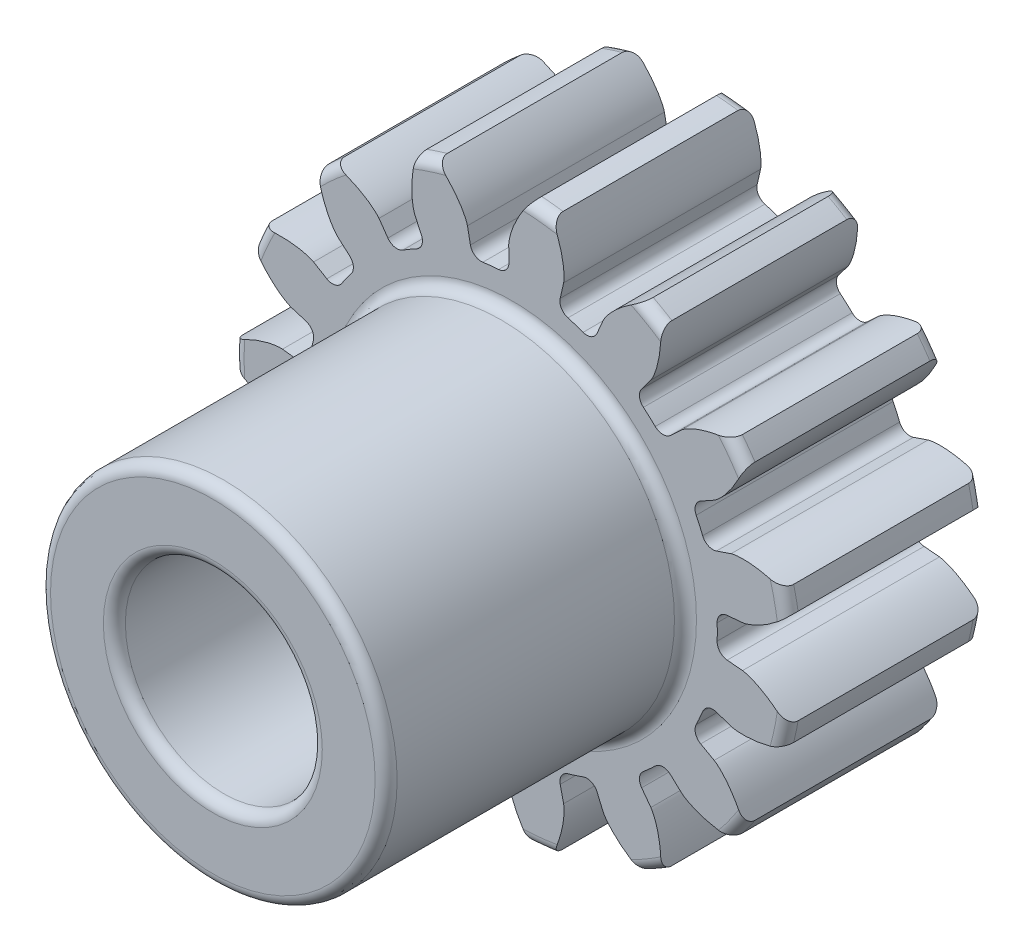
SolidWorks part; units mm, degrees
ref_plane "Front Plane" through (0, 0, 0) normal (0, 0, 1) x (1, 0, 0)
ref_plane "Top Plane" through (0, 0, 0) normal (0, 1, 0) x (1, 0, 0)
ref_plane "Right Plane" through (0, 0, 0) normal (1, 0, 0) x (0, 0, -1)
sketch "Sketch1" plane through (0, 0, 0) normal (0, 0, 1) x (1, 0, 0)
  line L0 (0, 0) -> (0, 3.9688) construction
  line L1 (-1.2755, 4.433) -> (1.2755, 3.5045) construction
  circle A0 centre (0, 0) radius 3.3073 construction
  circle A1 centre (0, 0) radius 4.4979 construction
  circle A2 centre (0, 0) radius 3.9688 construction
  circle A3 centre (0, 0) radius 3.7294 construction
  circle A4 centre (0, 0) radius 1.5875 construction
  circle A5 centre (0, 0) radius 2.794 construction
  point P8 (609.6, 0)
  point P13 (190.5, 0)
  dimension "OD | Outside Diameter" = 8.9958
  dimension "Root Diameter" = 6.6146
  dimension "Gear Pitch Diameter" = 7.9375
  dimension "Base Diameter" = 7.4588
  dimension "For Shaft Diameter" = 3.175
  dimension "Hub Diameter" = 5.588
  dimension "Pressure Angle" = 20
  dimension "Number of Teeth" = 381
  dimension "Gear Pitch | Diametral Pitch" = 1219.2
sketch "Sketch2" plane through (0, 0, 0) normal (1, 0, 0) x (0, 0, -1)
  line L0 (-4.0005, 0) -> (4.0005, 0) construction
  line L1 (-4.0005, 4.4979) -> (4.0005, 4.4979) construction
  point P2 (0, 4.4979)
  point P4 (0.8255, 0)
  point P6 (0.8255, 4.4979)
  dimension "Overall Width" = 8.001
  dimension "Hub Width" = 4.826
  dimension "Face Width" = 3.175
sketch "Sketch3" plane through (0, 0, 0) normal (0, 0, 1) x (1, 0, 0)
  circle A0 centre (0, 0) radius 4.4979
  circle A1 centre (0, 0) radius 4.4979 construction
extrude "Boss-Extrude1" add sketch "Sketch3" against normal up to vertex (4.0005 mm away) and the other way up to vertex (4.0005 mm away) up to point (0, 0, -4.0005) other way up to point (0, 0, 4.0005)
sketch "Sketch5" plane through (0, 0, 0) normal (1, 0, 0) x (0, 0, -1)
  line L1 (-4.0005, 4.4979) -> (0.8255, 4.4979)
  line L2 (-4.0005, 4.4979) -> (-4.0005, 2.794)
  line L3 (-4.0005, 2.794) -> (0.8255, 2.794)
  line L4 (0.8255, 4.4979) -> (0.8255, 2.794)
  line L11 (4.0005, 1.5875) -> (-4.0005, 1.5875)
  line L12 (4.0005, 1.5875) -> (4.0005, 0)
  line L13 (4.0005, 0) -> (-4.0005, 0)
  line L14 (-4.0005, 1.5875) -> (-4.0005, 0)
  point P5 (0, 1.5875)
  point P12 (0, 2.794)
revolve "Cut-Revolve1" cut sketch "Sketch5" angle 360 about L0
fillet "Fillet2" radius 0.1775 6 edges at (4.4979, 0, -4.0005) (1.5875, 0, -4.0005) (1.5875, 0, 4.0005) (2.794, 0, -0.8255) (4.4979, 0, -0.8255) (2.794, 0, 4.0005)
sketch "Sketch4" plane through (0, 0, 0) normal (0, 0, 1) x (1, 0, 0)
  line L0 (0, 0) -> (3.294, 0.2966) construction
  line L2 (0, 0) -> (3.294, -0.2966) construction
  line L4 (3.294, 0.2966) -> (3.7144, 0.3345)
  line L5 (3.7144, -0.3345) -> (3.294, -0.2966)
  arc A0 (3.294, 0.2966) -> (3.294, -0.2966) centre (0, 0) cw
  arc A3 (4.4324, 0.7646) -> (4.4324, -0.7646) centre (0, 0) cw
  circle A4 centre (0, 0) radius 4.4979 construction
  spline S0 degree 4 poles (3.7144, 0.3345) (3.7156, 0.3346) (3.7191, 0.3351) (3.7257, 0.3361) (3.7364, 0.338) (3.7499, 0.341) (3.7674, 0.3453) (3.7878, 0.3511) (3.8101, 0.3581) (3.8341, 0.3665) (3.858, 0.3755) (3.8817, 0.3851) (3.9051, 0.3952) (3.9333, 0.4081) (3.9668, 0.4244) (4.0056, 0.4448) (4.0491, 0.4694) (4.0929, 0.496) (4.1354, 0.5236) (4.1779, 0.5529) (4.2185, 0.5823) (4.2601, 0.6144) (4.2981, 0.6447) (4.34, 0.6803) (4.3736, 0.7095) (4.417, 0.7498) (4.4424, 0.7741) (4.4719, 0.8031) (4.4848, 0.8163) (4.4928, 0.8244) knots 0 0 0 0 0 0.005377 0.015084 0.028532 0.04661 0.064855 0.092111 0.119476 0.146842 0.174209 0.201575 0.228941 0.256307 0.307035 0.361767 0.4165 0.471232 0.525964 0.580697 0.635429 0.690161 0.744894 0.799626 0.854358 0.909091 0.954545 1 1 1 1 1 construction
  spline S1 degree 4 poles (3.7144, 0.3345) (3.7156, 0.3346) (3.7191, 0.3351) (3.7257, 0.3361) (3.7364, 0.338) (3.7499, 0.341) (3.7674, 0.3453) (3.7878, 0.3511) (3.8101, 0.3581) (3.8341, 0.3665) (3.858, 0.3755) (3.8817, 0.3851) (3.9051, 0.3952) (3.9333, 0.4081) (3.9668, 0.4244) (4.0056, 0.4448) (4.0491, 0.4694) (4.0929, 0.496) (4.1354, 0.5236) (4.1779, 0.5529) (4.2185, 0.5823) (4.2601, 0.6144) (4.2981, 0.6447) (4.34, 0.6803) (4.3736, 0.7095) (4.4076, 0.7411) (4.4241, 0.7566) (4.4324, 0.7646) knots 0 0 0 0 0 0.005377 0.015084 0.028532 0.04661 0.064855 0.092111 0.119476 0.146842 0.174209 0.201575 0.228941 0.256307 0.307035 0.361767 0.4165 0.471232 0.525964 0.580697 0.635429 0.690161 0.744894 0.799626 0.854358 0.909091 0.909091 0.909091 0.909091 0.909091
  spline S2 degree 4 poles (3.7144, -0.3345) (3.7156, -0.3346) (3.7191, -0.3351) (3.7257, -0.3361) (3.7364, -0.338) (3.7499, -0.341) (3.7674, -0.3453) (3.7878, -0.3511) (3.8101, -0.3581) (3.8341, -0.3665) (3.858, -0.3755) (3.8817, -0.3851) (3.9051, -0.3952) (3.9333, -0.4081) (3.9668, -0.4244) (4.0056, -0.4448) (4.0491, -0.4694) (4.0929, -0.496) (4.1354, -0.5236) (4.1779, -0.5529) (4.2185, -0.5823) (4.2601, -0.6144) (4.2981, -0.6447) (4.34, -0.6803) (4.3736, -0.7095) (4.417, -0.7498) (4.4424, -0.7741) (4.4719, -0.8031) (4.4848, -0.8163) (4.4928, -0.8244) knots 0 0 0 0 0 0.005377 0.015084 0.028532 0.04661 0.064855 0.092111 0.119476 0.146842 0.174209 0.201575 0.228941 0.256307 0.307035 0.361767 0.4165 0.471232 0.525964 0.580697 0.635429 0.690161 0.744894 0.799626 0.854358 0.909091 0.954545 1 1 1 1 1 construction
  spline S3 degree 4 poles (3.7144, -0.3345) (3.7156, -0.3346) (3.7191, -0.3351) (3.7257, -0.3361) (3.7364, -0.338) (3.7499, -0.341) (3.7674, -0.3453) (3.7878, -0.3511) (3.8101, -0.3581) (3.8341, -0.3665) (3.858, -0.3755) (3.8817, -0.3851) (3.9051, -0.3952) (3.9333, -0.4081) (3.9668, -0.4244) (4.0056, -0.4448) (4.0491, -0.4694) (4.0929, -0.496) (4.1354, -0.5236) (4.1779, -0.5529) (4.2185, -0.5823) (4.2601, -0.6144) (4.2981, -0.6447) (4.34, -0.6803) (4.3736, -0.7095) (4.4076, -0.7411) (4.4241, -0.7566) (4.4324, -0.7646) knots 0 0 0 0 0 0.005377 0.015084 0.028532 0.04661 0.064855 0.092111 0.119476 0.146842 0.174209 0.201575 0.228941 0.256307 0.307035 0.361767 0.4165 0.471232 0.525964 0.580697 0.635429 0.690161 0.744894 0.799626 0.854358 0.909091 0.909091 0.909091 0.909091 0.909091
  dimension "D1" = 6.6146
extrude "Cut-Extrude1" cut sketch "Sketch4" against normal through all both and the other way through all
fillet "Fillet1" radius 0.1775 2 edges at (3.294, -0.2966, -2.413) (3.294, 0.2966, -2.413)
pattern_circular "CirPattern1" count 15 over 360 about axis through (0, 0, 4.0005) along (0, 0, -1) of "Cut-Extrude1", "Fillet1"
equation "\"Root Diameter@Sketch1\"=\"Root Diameter\""
equation "\"OD | Outside Diameter@Sketch1\"=\"Outside Diameter\""
equation "\"D1@CirPattern1\"=\"Number of Teeth\""
equation "\"Diametral Pitch\"= 48"
equation "\"Number of Teeth\"= 15"
equation "\"Pressure Angle\"=20"
equation "\"Pitch Diameter\"= \"Number of Teeth\" / \"Diametral Pitch\""
equation "\"Base Diameter\"= \"Pitch Diameter\" * cos ( \"Pressure Angle\" )"
equation "\"Outside Diameter\"= ( \"Number of Teeth\" + 2 ) / \"Diametral Pitch\""
equation "\"Dedendum\"= 1.25 / \"Diametral Pitch\""
equation "\"Root Diameter\"= \"Pitch Diameter\" - ( 2 * \"Dedendum\" )"
equation "\"Pitch Angle\"= 360deg / \"Number of Teeth\""
equation "\"Alpha\"= sqr ( \"Pitch Diameter\" ^ 2 - \"Base Diameter\" ^ 2 ) / \"Base Diameter\" * 180 / PI - \"Pressure Angle\""
equation "\"Beta\"= ( \"Pitch Angle\" / 4 - \"Alpha\" )"
equation "\"Phi\"= sqr ( ( \"Outside Diameter\" / 2 ) ^ 2 - ( \"Base Diameter\" / 2 ) ^ 2 ) / ( \"Base Diameter\" / 2 )"
equation "\"Addendum\"= 1 / \"Diametral Pitch\""
equation "\"WorkingDepth\"= 2 / \"Diametral Pitch\""
equation "\"WholeDepth\"= 2.25 / \"Diametral Pitch\""
equation "\"Clearance\"= 0.25 / \"Diametral Pitch\""
equation "\"ToothThickness\"= ( pi * 2 ) / \"Diametral Pitch\""
equation "\"CircularPitch\"= pi / \"Diametral Pitch\""
equation "\"Number of Teeth@Sketch1\"=\"Number of Teeth\""
equation "\"Gear Pitch | Diametral Pitch@Sketch1\"=\"Diametral Pitch\""
equation "\"Pressure Angle@Sketch1\"=\"Pressure Angle\""
equation "\"Gear Pitch Diameter@Sketch1\"=\"Pitch Diameter\""
equation "\"Base Diameter@Sketch1\"=\"Base Diameter\""
equation "\"Fillet\"= \"Clearance\" * cos ( \"Pressure Angle\" ) * tan ( ( 90 + \"Pressure Angle\" ) / 2 )"
equation "\"D1@Fillet1\"=\"Fillet\""
equation "\"D1@Sketch4\"=if( \"Base Diameter\">\"Root Diameter\",\"Root Diameter\",\"Base Diameter\"-.00001)"
equation "\"D1@Fillet2\"=\"Fillet\""
